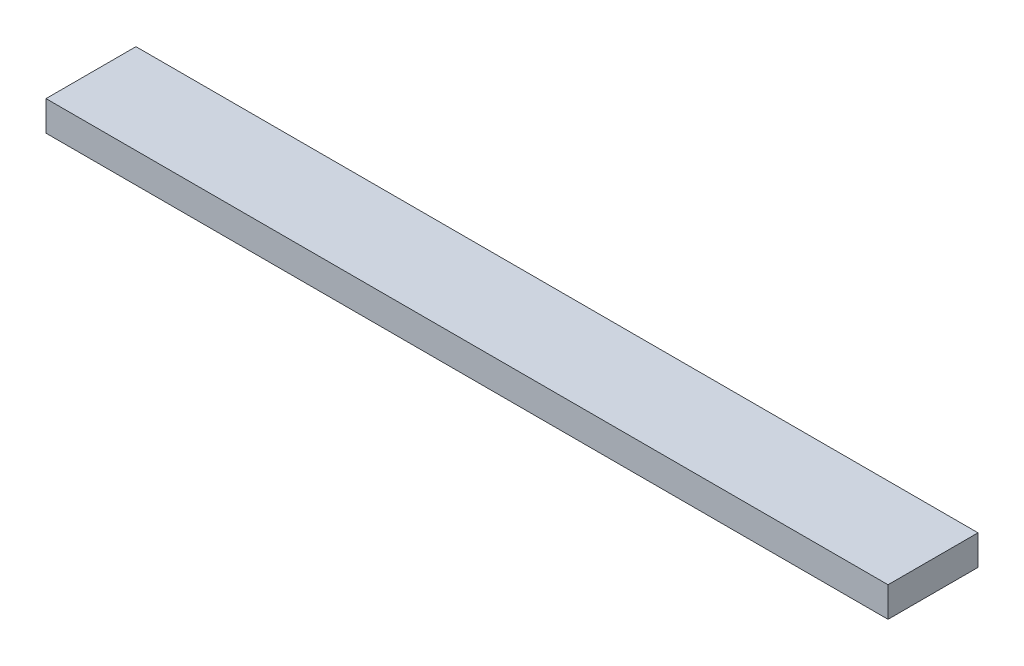
SolidWorks part; units mm, degrees
ref_plane "Front" through (0, 0, 0) normal (0, 0, 1) x (1, 0, 0)
ref_plane "Top" through (0, 0, 0) normal (0, 1, 0) x (1, 0, 0)
ref_plane "Right" through (0, 0, 0) normal (1, 0, 0) x (0, 0, -1)
sketch "Sketch1" plane through (0, 0, 0) normal (0, 1, 0) x (1, 0, 0)
  line L1 (0, 0) -> (2808, 0)
  line L2 (0, 0) -> (0, 300)
  line L3 (0, 300) -> (2808, 300)
  line L4 (2808, 0) -> (2808, 300)
  dimension "D1" = 2808
  dimension "D2" = 300
extrude "Boss-Extrude1" add sketch "Sketch1" along normal blind 100
